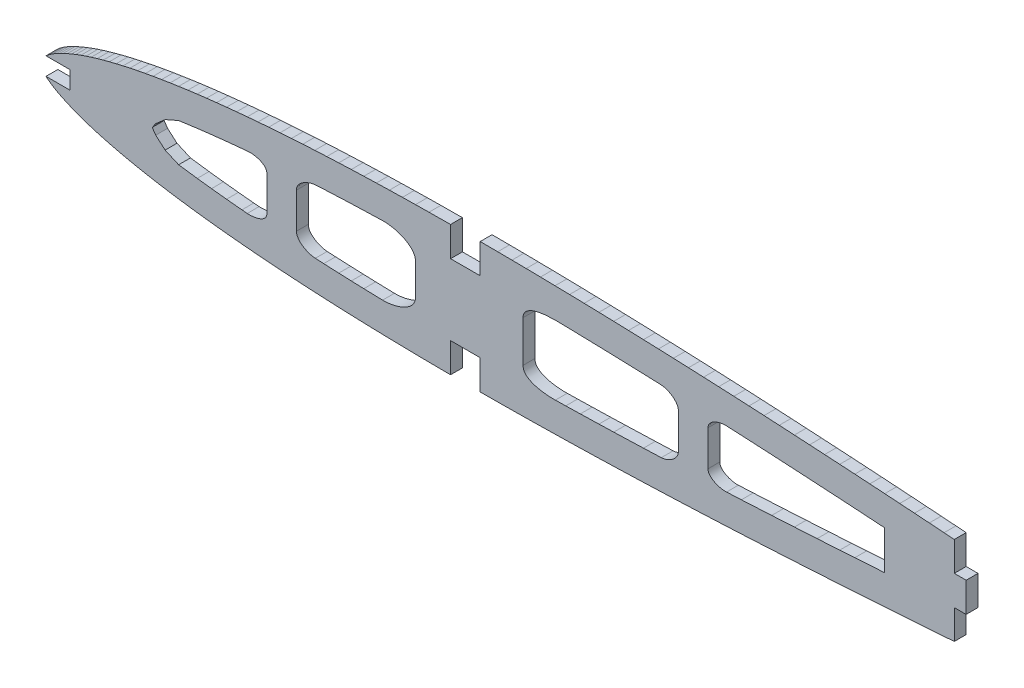
SolidWorks part; units mm, degrees
ref_plane "前视基准面" through (0, 0, 0) normal (0, 0, 1) x (1, 0, 0)
ref_plane "上视基准面" through (0, 0, 0) normal (0, 1, 0) x (1, 0, 0)
ref_plane "右视基准面" through (0, 0, 0) normal (1, 0, 0) x (0, 0, -1)
sketch "Model" plane through (0, 0, 0) normal (0, 0, 1) x (1, 0, 0)
  line L0 (365.1559, -97.3973) -> (369.2164, -97.3973)
  line L1 (369.2164, -97.3973) -> (369.2164, -100.3973)
  line L2 (369.2164, -100.3973) -> (365.1559, -100.3973)
  line L3 (438.4064, -87.9083) -> (438.4104, -92.9083)
  line L4 (438.4104, -92.9083) -> (433.4104, -92.9143)
  line L5 (433.4104, -92.9143) -> (433.4064, -87.9143)
  line L6 (438.4064, -109.8863) -> (438.4124, -104.8863)
  line L7 (438.4124, -104.8863) -> (433.4124, -104.8803)
  line L8 (433.4124, -104.8803) -> (433.4064, -109.8803)
  line L9 (518.3903, -91.444) -> (516.6664, -91.3183)
  line L10 (516.6664, -91.3183) -> (514.1714, -91.1393)
  line L11 (514.1714, -91.1393) -> (511.6764, -90.9633)
  line L12 (511.6764, -90.9633) -> (509.1804, -90.7903)
  line L13 (509.1804, -90.7903) -> (506.6554, -90.6183)
  line L14 (506.6554, -90.6183) -> (504.1314, -90.4503)
  line L15 (504.1314, -90.4503) -> (501.6054, -90.2873)
  line L16 (501.6054, -90.2873) -> (499.0594, -90.1283)
  line L17 (499.0594, -90.1283) -> (496.5144, -89.9743)
  line L18 (496.5144, -89.9743) -> (493.9684, -89.8233)
  line L19 (493.9684, -89.8233) -> (491.4134, -89.6743)
  line L20 (491.4134, -89.6743) -> (488.8584, -89.5283)
  line L21 (488.8584, -89.5283) -> (486.3034, -89.3863)
  line L22 (486.3034, -89.3863) -> (483.7484, -89.2513)
  line L23 (483.7484, -89.2513) -> (481.1944, -89.1213)
  line L24 (481.1944, -89.1213) -> (478.6384, -88.9983)
  line L25 (478.6384, -88.9983) -> (476.0924, -88.8813)
  line L26 (476.0924, -88.8813) -> (473.5474, -88.7693)
  line L27 (473.5474, -88.7693) -> (471.0014, -88.6633)
  line L28 (471.0014, -88.6633) -> (468.4764, -88.5643)
  line L29 (468.4764, -88.5643) -> (465.9524, -88.4703)
  line L30 (465.9524, -88.4703) -> (463.4264, -88.3833)
  line L31 (463.4264, -88.3833) -> (460.9314, -88.3033)
  line L32 (460.9314, -88.3033) -> (458.4364, -88.2303)
  line L33 (458.4364, -88.2303) -> (455.9404, -88.1633)
  line L34 (455.9404, -88.1633) -> (453.4854, -88.1043)
  line L35 (453.4854, -88.1043) -> (451.0314, -88.0523)
  line L36 (451.0314, -88.0523) -> (448.5764, -88.0073)
  line L37 (448.5764, -88.0073) -> (446.1704, -87.9703)
  line L38 (446.1704, -87.9703) -> (443.7664, -87.9423)
  line L39 (443.7664, -87.9423) -> (441.3604, -87.9213)
  line L40 (441.3604, -87.9213) -> (438.4064, -87.9083)
  line L42 (387.5324, -95.6683) -> (390.6644, -95.2413)
  line L43 (390.6644, -95.2413) -> (393.0784, -94.9513)
  line L44 (393.0784, -94.9513) -> (395.6144, -94.6733)
  line L45 (395.6144, -94.6733) -> (398.2099, -94.4193)
  line L46 (398.2099, -94.4193) -> (399.256, -94.3267)
  line L47 (410.7501, -93.5242) -> (412.0079, -93.4582)
  line L48 (412.0079, -93.4582) -> (414.9885, -93.3234)
  line L49 (414.9885, -93.3234) -> (416.6574, -93.2563)
  line L50 (416.6574, -93.2563) -> (418.7714, -93.1823)
  line L51 (418.7714, -93.1823) -> (421.9864, -93.0883)
  line L52 (421.9343, -104.7047) -> (418.7714, -104.6123)
  line L53 (418.7714, -104.6123) -> (416.6574, -104.5383)
  line L54 (416.6574, -104.5383) -> (414.5434, -104.4533)
  line L55 (414.5434, -104.4533) -> (412.0079, -104.3363)
  line L56 (412.0079, -104.3363) -> (410.5909, -104.2619)
  line L57 (399.1076, -103.4547) -> (398.2099, -103.3753)
  line L58 (398.2099, -103.3753) -> (395.6144, -103.1213)
  line L59 (395.6144, -103.1213) -> (393.0784, -102.8433)
  line L60 (393.0784, -102.8433) -> (390.6644, -102.5533)
  line L61 (390.6644, -102.5533) -> (387.5324, -102.1263)
  line L62 (451.3201, -93.0601) -> (452.8362, -93.0905)
  line L63 (452.8362, -93.0905) -> (455.2997, -93.1479)
  line L64 (455.2997, -93.1479) -> (458.4364, -93.2303)
  line L65 (458.4364, -93.2303) -> (460.9314, -93.3033)
  line L66 (460.9314, -93.3033) -> (465.9524, -93.4703)
  line L67 (465.9524, -93.4703) -> (468.8582, -93.5804)
  line L68 (479.9184, -94.063) -> (482.4714, -94.1863)
  line L69 (482.4714, -94.1863) -> (487.5809, -94.4573)
  line L70 (487.5809, -94.4573) -> (491.4134, -94.6743)
  line L71 (491.4134, -94.6743) -> (495.2414, -94.8988)
  line L72 (495.2414, -94.8988) -> (499.0594, -95.1283)
  line L73 (499.0594, -95.1283) -> (501.6054, -95.2873)
  line L74 (501.6054, -95.2873) -> (506.6554, -95.6183)
  line L75 (506.6554, -102.1763) -> (501.6054, -102.5073)
  line L76 (501.6054, -102.5073) -> (499.0594, -102.6663)
  line L77 (499.0594, -102.6663) -> (495.2414, -102.8958)
  line L78 (495.2414, -102.8958) -> (491.4134, -103.1203)
  line L79 (491.4134, -103.1203) -> (487.5809, -103.3373)
  line L80 (487.5809, -103.3373) -> (482.4714, -103.6083)
  line L81 (482.4714, -103.6083) -> (479.9656, -103.7292)
  line L82 (468.9559, -104.2104) -> (465.9524, -104.3243)
  line L83 (465.9524, -104.3243) -> (460.9314, -104.4913)
  line L84 (460.9314, -104.4913) -> (458.4364, -104.5643)
  line L85 (458.4364, -104.5643) -> (455.2997, -104.6467)
  line L86 (455.2997, -104.6467) -> (452.8362, -104.704)
  line L87 (452.8362, -104.704) -> (451.0861, -104.7391)
  line L88 (387.5324, -95.6683) -> (385.2532, -96.6702)
  line L89 (385.2532, -96.6702) -> (383.6712, -98.0522)
  line L90 (383.6712, -98.0522) -> (383.078, -98.8973)
  line L91 (387.5324, -102.1263) -> (385.2532, -101.1243)
  line L92 (385.2532, -101.1243) -> (383.6712, -99.7423)
  line L93 (383.6712, -99.7423) -> (383.078, -98.8973)
  line L94 (427.4864, -96.2466) -> (427.4864, -101.548)
  line L95 (445.635, -95.4141) -> (445.635, -102.3805)
  line L96 (407.4071, -95.8973) -> (407.4071, -101.8973)
  line L97 (402.4071, -101.8973) -> (402.4071, -95.8973)
  line L98 (476.8379, -95.8973) -> (476.8379, -101.8973)
  line L99 (471.8379, -101.8973) -> (471.8379, -95.8973)
  line L100 (520.3903, -98.8973) -> (520.3903, -96.3973)
  line L101 (520.3903, -98.8973) -> (520.3903, -101.3973)
  line L102 (520.3903, -96.3973) -> (518.3903, -96.3973)
  line L103 (520.3903, -101.3973) -> (518.3903, -101.3973)
  line L104 (518.3903, -96.3973) -> (518.3903, -91.444)
  line L105 (518.3903, -101.3973) -> (518.3903, -106.3499)
  line L106 (506.6554, -95.6183) -> (506.6554, -102.1763)
  line L107 (433.4064, -87.9143) -> (429.7654, -87.9423)
  line L108 (429.7654, -87.9423) -> (427.4864, -87.9723)
  line L109 (427.4864, -87.9723) -> (425.2864, -88.0113)
  line L110 (425.2864, -88.0113) -> (423.0864, -88.0593)
  line L111 (423.0864, -88.0593) -> (420.8864, -88.1173)
  line L112 (420.8864, -88.1173) -> (418.7714, -88.1823)
  line L113 (418.7714, -88.1823) -> (416.6574, -88.2563)
  line L114 (416.6574, -88.2563) -> (414.5434, -88.3413)
  line L115 (414.5434, -88.3413) -> (412.5224, -88.4323)
  line L116 (412.5224, -88.4323) -> (410.5024, -88.5343)
  line L117 (410.5024, -88.5343) -> (408.4824, -88.6463)
  line L118 (408.4824, -88.6463) -> (406.5644, -88.7643)
  line L119 (406.5644, -88.7643) -> (404.6474, -88.8943)
  line L120 (404.6474, -88.8943) -> (402.7304, -89.0353)
  line L121 (402.7304, -89.0353) -> (400.9214, -89.1793)
  line L122 (400.9214, -89.1793) -> (399.1134, -89.3353)
  line L123 (399.1134, -89.3353) -> (397.3064, -89.5033)
  line L124 (397.3064, -89.5033) -> (395.6144, -89.6733)
  line L125 (395.6144, -89.6733) -> (393.9234, -89.8543)
  line L126 (393.9234, -89.8543) -> (392.2334, -90.0483)
  line L127 (392.2334, -90.0483) -> (390.6644, -90.2413)
  line L128 (390.6644, -90.2413) -> (389.0974, -90.4483)
  line L129 (389.0974, -90.4483) -> (387.5324, -90.6683)
  line L130 (387.5324, -90.6683) -> (386.0934, -90.8853)
  line L131 (386.0934, -90.8853) -> (384.6574, -91.1153)
  line L132 (384.6574, -91.1153) -> (383.2234, -91.3593)
  line L133 (383.2234, -91.3593) -> (381.9184, -91.5963)
  line L134 (381.9184, -91.5963) -> (380.6174, -91.8473)
  line L135 (380.6174, -91.8473) -> (379.3184, -92.1143)
  line L136 (379.3184, -92.1143) -> (378.1544, -92.3693)
  line L137 (378.1544, -92.3693) -> (376.9934, -92.6403)
  line L138 (376.9934, -92.6403) -> (375.8364, -92.9273)
  line L139 (375.8364, -92.9273) -> (374.8164, -93.1963)
  line L140 (374.8164, -93.1963) -> (373.8004, -93.4803)
  line L141 (373.8004, -93.4803) -> (372.7894, -93.7843)
  line L142 (372.7894, -93.7843) -> (371.9164, -94.0643)
  line L143 (371.9164, -94.0643) -> (371.0504, -94.3633)
  line L144 (371.0504, -94.3633) -> (370.1914, -94.6823)
  line L145 (370.1914, -94.6823) -> (369.4714, -94.9713)
  line L146 (369.4714, -94.9713) -> (368.7584, -95.2773)
  line L147 (368.7584, -95.2773) -> (368.0524, -95.6003)
  line L148 (368.0524, -95.6003) -> (367.4844, -95.8783)
  line L149 (367.4844, -95.8783) -> (366.9254, -96.1743)
  line L150 (366.9254, -96.1743) -> (366.3794, -96.4943)
  line L151 (366.3794, -96.4943) -> (365.9634, -96.7673)
  line L152 (365.9634, -96.7673) -> (365.5614, -97.0603)
  line L153 (365.5614, -97.0603) -> (365.1784, -97.3763)
  line L154 (365.1784, -97.3763) -> (365.1559, -97.3973)
  line L155 (438.4064, -109.8863) -> (441.3604, -109.8723)
  line L156 (441.3604, -109.8723) -> (443.7664, -109.8523)
  line L157 (443.7664, -109.8523) -> (446.1704, -109.8233)
  line L158 (446.1704, -109.8233) -> (448.5764, -109.7873)
  line L159 (448.5764, -109.7873) -> (451.0314, -109.7423)
  line L160 (451.0314, -109.7423) -> (453.4854, -109.6903)
  line L161 (453.4854, -109.6903) -> (455.9404, -109.6313)
  line L162 (455.9404, -109.6313) -> (458.4364, -109.5643)
  line L163 (458.4364, -109.5643) -> (460.9314, -109.4913)
  line L164 (460.9314, -109.4913) -> (463.4264, -109.4113)
  line L165 (463.4264, -109.4113) -> (465.9524, -109.3233)
  line L166 (465.9524, -109.3233) -> (468.4764, -109.2303)
  line L167 (468.4764, -109.2303) -> (471.0014, -109.1303)
  line L168 (471.0014, -109.1303) -> (473.5474, -109.0243)
  line L169 (473.5474, -109.0243) -> (476.0924, -108.9133)
  line L170 (476.0924, -108.9133) -> (478.6384, -108.7963)
  line L171 (478.6384, -108.7963) -> (481.1944, -108.6723)
  line L172 (481.1944, -108.6723) -> (483.7484, -108.5433)
  line L173 (483.7484, -108.5433) -> (486.3034, -108.4073)
  line L174 (486.3034, -108.4073) -> (488.8584, -108.2663)
  line L175 (488.8584, -108.2663) -> (491.4134, -108.1203)
  line L176 (491.4134, -108.1203) -> (493.9684, -107.9703)
  line L177 (493.9684, -107.9703) -> (496.5144, -107.8193)
  line L178 (496.5144, -107.8193) -> (499.0594, -107.6653)
  line L179 (499.0594, -107.6653) -> (501.6054, -107.5063)
  line L180 (501.6054, -107.5063) -> (504.1314, -107.3433)
  line L181 (504.1314, -107.3433) -> (506.6554, -107.1753)
  line L182 (506.6554, -107.1753) -> (509.1804, -107.0033)
  line L183 (509.1804, -107.0033) -> (511.6764, -106.8313)
  line L184 (511.6764, -106.8313) -> (514.1714, -106.6553)
  line L185 (514.1714, -106.6553) -> (516.6664, -106.4763)
  line L186 (516.6664, -106.4763) -> (518.3903, -106.3499)
  line L187 (365.1559, -100.3973) -> (365.1784, -100.4183)
  line L188 (365.1784, -100.4183) -> (365.5614, -100.7343)
  line L189 (365.5614, -100.7343) -> (365.9634, -101.0273)
  line L190 (365.9634, -101.0273) -> (366.3794, -101.2993)
  line L191 (366.3794, -101.2993) -> (366.9254, -101.6203)
  line L192 (366.9254, -101.6203) -> (367.4844, -101.9153)
  line L193 (367.4844, -101.9153) -> (368.0524, -102.1933)
  line L194 (368.0524, -102.1933) -> (368.7584, -102.5173)
  line L195 (368.7584, -102.5173) -> (369.4714, -102.8233)
  line L196 (369.4714, -102.8233) -> (370.1914, -103.1113)
  line L197 (370.1914, -103.1113) -> (371.0504, -103.4313)
  line L198 (371.0504, -103.4313) -> (371.9164, -103.7293)
  line L199 (371.9164, -103.7293) -> (372.7894, -104.0103)
  line L200 (372.7894, -104.0103) -> (373.8004, -104.3133)
  line L201 (373.8004, -104.3133) -> (374.8164, -104.5983)
  line L202 (374.8164, -104.5983) -> (375.8364, -104.8673)
  line L203 (375.8364, -104.8673) -> (376.9934, -105.1543)
  line L204 (376.9934, -105.1543) -> (378.1544, -105.4253)
  line L205 (378.1544, -105.4253) -> (379.3184, -105.6803)
  line L206 (379.3184, -105.6803) -> (380.6174, -105.9473)
  line L207 (380.6174, -105.9473) -> (381.9184, -106.1983)
  line L208 (381.9184, -106.1983) -> (383.2234, -106.4343)
  line L209 (383.2234, -106.4343) -> (384.6574, -106.6793)
  line L210 (384.6574, -106.6793) -> (386.0934, -106.9093)
  line L211 (386.0934, -106.9093) -> (387.5324, -107.1253)
  line L212 (387.5324, -107.1253) -> (389.0974, -107.3463)
  line L213 (389.0974, -107.3463) -> (390.6644, -107.5523)
  line L214 (390.6644, -107.5523) -> (392.2334, -107.7463)
  line L215 (392.2334, -107.7463) -> (393.9234, -107.9403)
  line L216 (393.9234, -107.9403) -> (395.6144, -108.1213)
  line L217 (395.6144, -108.1213) -> (397.3064, -108.2903)
  line L218 (397.3064, -108.2903) -> (399.1134, -108.4583)
  line L219 (399.1134, -108.4583) -> (400.9214, -108.6143)
  line L220 (400.9214, -108.6143) -> (402.7304, -108.7593)
  line L221 (402.7304, -108.7593) -> (404.6474, -108.9003)
  line L222 (404.6474, -108.9003) -> (406.5644, -109.0293)
  line L223 (406.5644, -109.0293) -> (408.4824, -109.1473)
  line L224 (408.4824, -109.1473) -> (410.5024, -109.2603)
  line L225 (410.5024, -109.2603) -> (412.5224, -109.3613)
  line L226 (412.5224, -109.3613) -> (414.5434, -109.4523)
  line L227 (414.5434, -109.4523) -> (416.6574, -109.5373)
  line L228 (416.6574, -109.5373) -> (418.7714, -109.6123)
  line L229 (418.7714, -109.6123) -> (420.8864, -109.6773)
  line L230 (420.8864, -109.6773) -> (423.0864, -109.7353)
  line L231 (423.0864, -109.7353) -> (425.2864, -109.7833)
  line L232 (425.2864, -109.7833) -> (427.4864, -109.8213)
  line L233 (427.4864, -109.8213) -> (429.7654, -109.8513)
  line L234 (429.7654, -109.8513) -> (433.4064, -109.8803)
  spline S0 degree 3 poles (421.9864, -93.0883) (424.0996, -93.0265) (427.4864, -94.1325) (427.4864, -96.2466) knots 0 0 0 0 6.342328 6.342328 6.342328 6.342328
  spline S1 degree 3 poles (421.9343, -104.7047) (424.0623, -104.767) (427.4864, -103.6769) (427.4864, -101.548) knots 0 0 0 0 6.386793 6.386793 6.386793 6.386793
  spline S2 degree 3 poles (445.635, -95.4141) (445.635, -93.363) (449.2694, -93.019) (451.3201, -93.0601) knots 0 0 0 0 6.153175 6.153175 6.153175 6.153175
  spline S3 degree 3 poles (445.635, -102.3805) (445.635, -104.3603) (449.1067, -104.7787) (451.0861, -104.7391) knots 0 0 0 0 5.93954 5.93954 5.93954 5.93954
  spline S4 degree 3 poles (399.256, -94.3267) (400.425, -94.2232) (402.4071, -94.7237) (402.4071, -95.8973) knots 0 0 0 0 3.52078 3.52078 3.52078 3.52078
  spline S5 degree 3 poles (399.1076, -103.4547) (400.319, -103.5619) (402.4071, -103.1135) (402.4071, -101.8973) knots 0 0 0 0 3.648605 3.648605 3.648605 3.648605
  spline S6 degree 3 poles (410.7501, -93.5242) (409.3855, -93.5959) (407.4071, -94.5307) (407.4071, -95.8973) knots 0 0 0 0 4.09968 4.09968 4.09968 4.09968
  spline S7 degree 3 poles (410.5909, -104.2619) (409.2708, -104.1926) (407.4071, -103.2192) (407.4071, -101.8973) knots 0 0 0 0 3.965934 3.965934 3.965934 3.965934
  spline S8 degree 3 poles (468.8582, -93.5804) (470.1154, -93.628) (471.8379, -94.6391) (471.8379, -95.8973) knots 0 0 0 0 3.774504 3.774504 3.774504 3.774504
  spline S9 degree 3 poles (468.9559, -104.2104) (470.1869, -104.1638) (471.8379, -103.1291) (471.8379, -101.8973) knots 0 0 0 0 3.695535 3.695535 3.695535 3.695535
  spline S10 degree 3 poles (479.9184, -94.063) (478.7247, -94.0054) (476.8379, -94.7022) (476.8379, -95.8973) knots 0 0 0 0 3.585193 3.585193 3.585193 3.585193
  spline S11 degree 3 poles (479.9656, -103.7292) (478.7588, -103.7875) (476.8379, -103.1055) (476.8379, -101.8973) knots 0 0 0 0 3.624712 3.624712 3.624712 3.624712
  point P36 (0, 0)
  point P249 (518.451, -91.4621)
  point P250 (0, 0)
extrude "凸台-拉伸1" add sketch "Model" along normal blind 2
